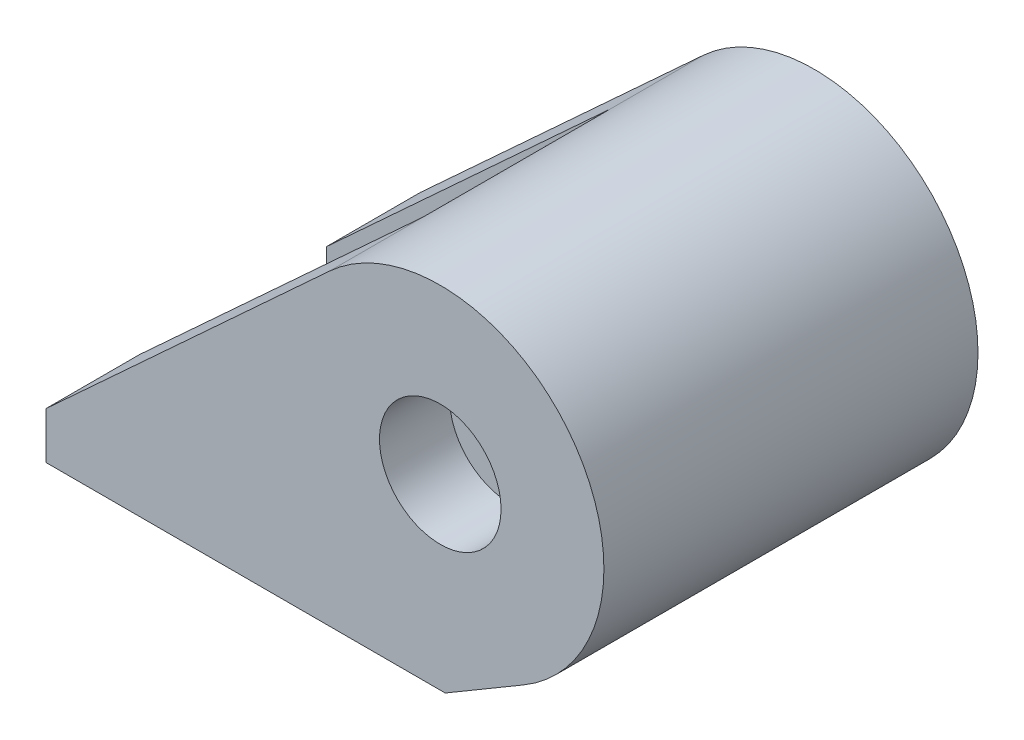
SolidWorks part; units mm, degrees
ref_plane "Спереди" through (0, 0, 0) normal (0, 0, 1) x (1, 0, 0)
ref_plane "Сверху" through (0, 0, 0) normal (0, 1, 0) x (1, 0, 0)
ref_plane "Справа" through (0, 0, 0) normal (1, 0, 0) x (0, 0, -1)
sketch "Эскиз1" plane through (0, 0, 0) normal (0, 0, 1) x (1, 0, 0)
  line L0 (0, 35) -> (-84.5144, 35) construction
  line L1 (0, 0) -> (35, 0) construction
  line L2 (35, 0) -> (35, -40) construction
  line L3 (35, -40) -> (-84.3144, -40) construction
  line L4 (-84.3144, -40) -> (-84.3144, -30) construction
  line L5 (-84.3144, -30) -> (-23.6946, 25.7598)
  line L6 (-84.3144, -30) -> (-84.3144, -40)
  line L7 (-84.3144, -40) -> (1.0606, -40)
  line L8 (0, 0) -> (0, -46.2136) construction
  line L9 (1.0606, -40) -> (17.7692, -30.1538)
  arc A0 (17.7692, -30.1538) -> (-23.6946, 25.7598) centre (0, 0) ccw
  point P15 (0, 0)
  dimension "D1" = 40
  dimension "D2" = 70
  dimension "D3" = 1.0606
  dimension "D4" = 10
  dimension "D5" = 23.6946
extrude "Бобышка-Вытянуть1" add sketch "Эскиз1" along normal blind 80
sketch "Эскиз2" plane through (0, 0, 0) normal (0, 0, 1) x (1, 0, 0)
  circle A0 centre (0, 0) radius 13
  dimension "D1" = 26
extrude "Вырез-Вытянуть2" cut sketch "Эскиз2" along normal blind 15
sketch "Эскиз4" plane through (0, 0, 80) normal (0, 0, 1) x (1, 0, 0)
  circle A0 centre (0, 0) radius 13
  dimension "D1" = 26
extrude "Вырез-Вытянуть3" cut sketch "Эскиз4" against normal blind 15
sketch "Эскиз5" plane through (0, 0, 0) normal (0, 1, 0) x (1, 0, 0)
  line L0 (-84.3144, 0) -> (-84.3144, -80) construction
  line L1 (-84.3144, -80) -> (-23.6946, -80) construction
  line L2 (-23.6946, -80) -> (-23.6946, 0) construction
  line L3 (-23.6946, 0) -> (-84.3144, 0) construction
  line L4 (-84.3144, 0) -> (-84.3144, -20) construction
  line L5 (-84.3144, -20) -> (-64.3144, -20) construction
  line L6 (-64.3144, -20) -> (-64.3144, -60) construction
  line L7 (-64.3144, -60) -> (-84.3144, -60) construction
  line L9 (-84.3144, -20) -> (-64.3144, -20)
  line L10 (-84.3144, -20) -> (-84.3144, -60)
  line L11 (-84.3144, -60) -> (-64.3144, -60)
  line L12 (-64.3144, -20) -> (-64.3144, -60)
  dimension "D1" = 64.3144
  dimension "D2" = 60
extrude "Вырез-Вытянуть4" cut sketch "Эскиз5" against normal through all both and the other way through all
sketch "Эскиз6" plane through (0, 0, 0) normal (0, 1, 0) x (1, 0, 0)
  line L1 (-84.3144, -80) -> (-23.6946, -80) construction
  line L2 (-23.6946, -80) -> (-23.6946, 0) construction
  line L3 (35, 0) -> (-23.6946, 0) construction
  line L4 (-23.6946, -80) -> (-23.6946, 0) construction
  line L5 (-23.6946, 0) -> (-84.3144, 0) construction
  line L9 (-55, -25) -> (-84.3144, -25)
  line L10 (-84.3144, -25) -> (-84.3144, -55)
  line L12 (-84.3144, -55) -> (-55, -55)
  arc A2 (-55, -55) -> (-55, -25) centre (-55, -40) ccw
  dimension "D1" = 15
  dimension "D2" = 55
  dimension "D3" = 40
extrude "Вырез-Вытянуть6" cut sketch "Эскиз6" against normal blind 24 and the other way through all
sketch "Эскиз9" plane through (0, -24, 0) normal (0, 1, 0) x (1, 0, 0)
  line L0 (-55, -48) -> (-92.7334, -48)
  line L1 (-92.7334, -48) -> (-92.7334, -32)
  line L2 (-92.7334, -32) -> (-55, -32)
  line L3 (-64.3144, -25) -> (-64.3144, -55) construction
  arc A0 (-55, -48) -> (-55, -32) centre (-55, -40) ccw
  dimension "D1" = 8
  dimension "D2" = 28.419
extrude "Вырез-Вытянуть7" cut sketch "Эскиз9" against normal through all
sketch "Эскиз10" plane through (0, 0, 0) normal (0, 1, 0) x (1, 0, 0)
  line L1 (-64.3144, -20) -> (-34.3144, -20)
  line L2 (-64.3144, -20) -> (-64.3144, -60)
  line L3 (-64.3144, -60) -> (-34.3144, -60)
  line L4 (-34.3144, -20) -> (-34.3144, -60)
  point P5 (-127.5746, -63.907)
  dimension "D1" = 34.3144
  dimension "D2" = 60
extrude "Вырез-Вытянуть8" cut sketch "Эскиз10" against normal blind 24 and the other way blind 32
sketch "Эскиз11" plane through (0, -24, 0) normal (0, 1, 0) x (1, 0, 0)
  line L0 (-34.3144, -60) -> (-34.3144, -20) construction
  line L1 (-55, -25) -> (-81.861, -25)
  line L3 (-55, -55) -> (-81.861, -55)
  line L4 (-81.861, -25) -> (-81.861, -55)
  arc A0 (-55, -55) -> (-55, -25) centre (-55, -40) ccw
  dimension "D1" = 15
  dimension "D2" = 47.5466
extrude "Вырез-Вытянуть9" cut sketch "Эскиз11" against normal blind 6
sketch "Эскиз12" plane through (0, 0, 0) normal (0, 0, 1) x (1, 0, 0)
  line L0 (-35, 0) -> (-35, -24)
  line L1 (-52.9502, 0) -> (37.7357, 0) construction
  line L2 (-35, -24) -> (-25.4755, -24)
  arc A0 (-25.4755, -24) -> (-35, 0) centre (0, 0) ccw
  dimension "D1" = 35
  dimension "D2" = 25.4755
sketch "Эскиз13" plane through (0, -24, 0) normal (0, 1, 0) x (1, 0, 0)
  line L0 (-23.6946, -80) -> (-23.6946, 0) construction
  line L1 (-34.3144, -20) -> (-23.6946, -20)
  line L2 (-34.3144, -20) -> (-34.3144, -60)
  line L3 (-34.3144, -60) -> (-23.6946, -60)
  line L4 (-23.6946, -20) -> (-23.6946, -60)
  line L5 (-34.3144, -60) -> (-34.3144, -20) construction
  dimension "D1" = 40
extrude "Вырез-Вытянуть10" cut sketch "Эскиз13" along normal blind 71
extrude "Бобышка-Вытянуть3" add sketch "Эскиз12" along normal blind 60
